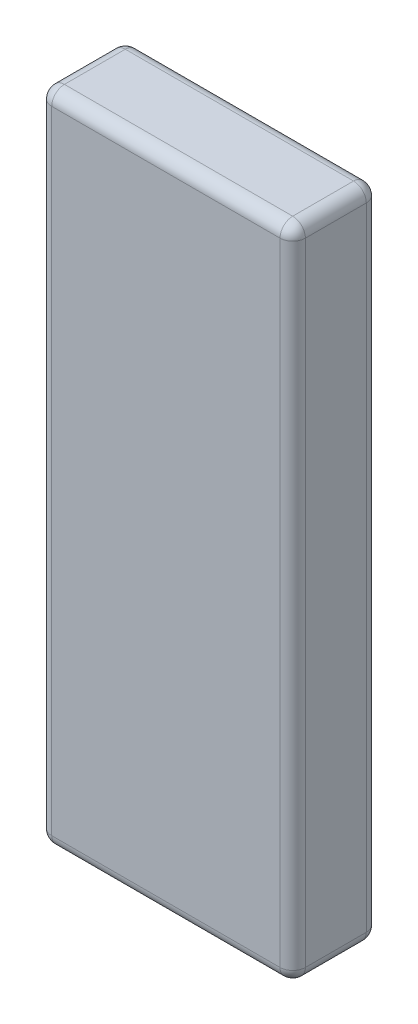
SolidWorks part; units mm, degrees
ref_plane "Спереди" through (0, 0, 0) normal (0, 0, 1) x (1, 0, 0)
ref_plane "Сверху" through (0, 0, 0) normal (0, 1, 0) x (1, 0, 0)
ref_plane "Справа" through (0, 0, 0) normal (1, 0, 0) x (0, 0, -1)
sketch "Эскиз1" plane through (0, 0, 0) normal (0, 0, 1) x (1, 0, 0)
  line L1 (0, 0) -> (20, 0)
  line L2 (0, 0) -> (0, 51.8)
  line L3 (0, 51.8) -> (20, 51.8)
  line L4 (20, 0) -> (20, 51.8)
  dimension "D1" = 51.8
  dimension "D2" = 20
extrude "Бобышка-Вытянуть1" add sketch "Эскиз1" along normal blind 6.8
fillet "Скругление1" radius 1 12 edges at (0, 0, 3.4) (20, 0, 3.4) (20, 51.8, 3.4) (0, 51.8, 3.4) (10, 0, 0) (20, 25.9, 0) (10, 51.8, 0) (0, 25.9, 0) (10, 51.8, 6.8) (20, 25.9, 6.8) (10, 0, 6.8) (0, 25.9, 6.8)
